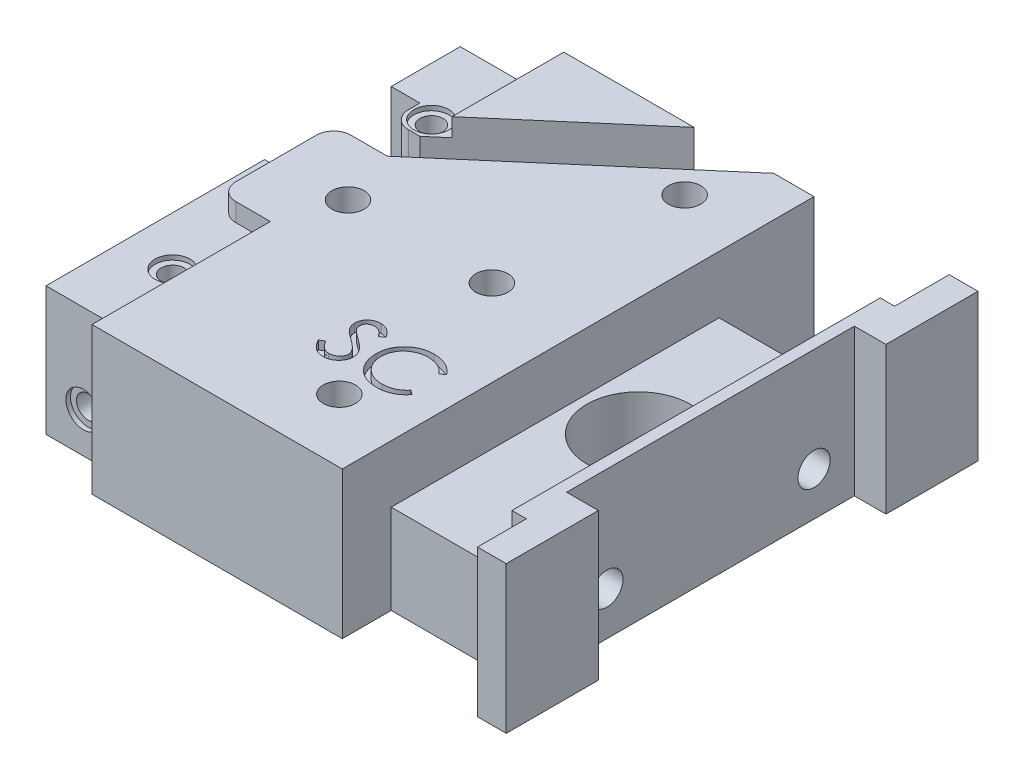
SolidWorks part; units mm, degrees
ref_plane "Plan de face" through (0, 0, 0) normal (0, 0, 1) x (1, 0, 0)
ref_plane "Plan de dessus" through (0, 0, 0) normal (0, 1, 0) x (1, 0, 0)
ref_plane "Plan de droite" through (0, 0, 0) normal (1, 0, 0) x (0, 0, -1)
sketch "Esquisse7" plane through (0, 0, 0) normal (0, 0, 1) x (1, 0, 0)
  line L2 (0, 0) -> (85, 0)
  line L3 (85, 0) -> (85, 25.55)
  line L5 (0, 25.55) -> (0, 0)
  line L6 (0, 25.55) -> (56.5, 25.55)
  line L7 (56.5, 25.55) -> (56.5, 15.55)
  line L8 (56.5, 15.55) -> (77.5, 15.55)
  line L9 (77.5, 15.55) -> (77.5, 25.55)
  line L10 (77.5, 25.55) -> (85, 25.55)
  dimension "D1" = 85
  dimension "D2" = 7.5
  dimension "D3" = 25.55
  dimension "D6" = 21
  dimension "D7" = 10
extrude "Boss.-Extru.3" add sketch "Esquisse7" along normal mid plane 82
sketch "Esquisse8" plane through (85, 0, 0) normal (1, 0, 0) x (0, 0, -1)
  line L0 (-41, 0) -> (41, 0) construction
  line L1 (-25, 0) -> (25, 0)
  line L2 (-25, 0) -> (-25, 25.55)
  line L3 (-25, 25.55) -> (25, 25.55)
  line L4 (25, 0) -> (25, 25.55)
  line L5 (-41, 25.55) -> (41, 25.55) construction
  point P8 (0, 0)
  point P9 (0, 0)
  dimension "D1" = 50
extrude "Enlèv. mat.-Extru.1" cut sketch "Esquisse8" against normal blind 5.5
sketch "Esquisse9" plane through (0, 15.55, 0) normal (0, 1, 0) x (1, 0, 0)
  line L0 (85, 25) -> (85, 41) construction
  circle A0 centre (67, 0) radius 9
  point P4 (85, 33)
  point P5 (67, 0)
  dimension "D1" = 18
  dimension "D2" = 18
extrude "Enlèv. mat.-Extru.2" cut sketch "Esquisse9" against normal through all
sketch "Esquisse10" plane through (0, 15.55, 0) normal (0, 1, 0) x (1, 0, 0)
  line L0 (56.5, -41) -> (56.5, 41) construction
  line L1 (77.5, 41) -> (56.5, 41)
  line L2 (77.5, 41) -> (77.5, 31.5)
  line L3 (77.5, 31.5) -> (56.5, 31.5)
  line L4 (56.5, 41) -> (56.5, 31.5)
  line L5 (56.5, 41) -> (0, 41) construction
  dimension "D1" = 9.5
  dimension "D2" = 21
extrude "Enlèv. mat.-Extru.3" cut sketch "Esquisse10" against normal through all
chamfer "Chanfrein1" distance 7 angle 45 1 edges at (67, 15.55, -31.5)
sketch "Esquisse13" plane through (0, 0, 41) normal (0, 0, 1) x (1, 0, 0)
  line L0 (0, 0) -> (85, 0) construction
  line L1 (56.5, 14) -> (77.5, 14)
  line L2 (56.5, 14) -> (56.5, 0)
  line L3 (56.5, 0) -> (77.5, 0)
  line L4 (77.5, 14) -> (77.5, 0)
  line L5 (77.5, 25.55) -> (77.5, 15.55) construction
  dimension "D1" = 21
  dimension "D2" = 14
extrude "Enlèv. mat.-Extru.5" [suppressed] cut sketch "Esquisse13" against normal blind 8.5
chamfer "Chanfrein2" [suppressed] distance 7 angle 45
sketch "Esquisse14" plane through (0, 25.55, 0) normal (0, 1, 0) x (1, 0, 0)
  line L0 (0, -41) -> (0, 41) construction
  line L1 (0, 41) -> (13, 41)
  line L2 (0, 41) -> (0, 10)
  line L3 (4, 10) -> (13, 10)
  line L4 (13, 41) -> (13, 10)
  line L5 (0, 0) -> (4, 0)
  line L6 (0, 0) -> (0, 10)
  line L8 (4, 0) -> (4, 10)
  dimension "D1" = 13
  dimension "D2" = 31
  dimension "D3" = 4
extrude "Enlèv. mat.-Extru.6" cut sketch "Esquisse14" against normal blind 3.175
sketch "Esquisse33" plane through (0, 0, 0) normal (-1, 0, 0) x (0, 0, 1)
  line L0 (41, 0) -> (-41, 0) construction
  line L1 (-24, 22.375) -> (-2, 22.375)
  line L2 (-24, 22.375) -> (-24, 0)
  line L3 (-24, 0) -> (-2, 0)
  line L4 (-2, 22.375) -> (-2, 0)
  line L5 (-41, 22.375) -> (0, 22.375) construction
  dimension "D2" = 22
  dimension "D3" = 2
extrude "Enlèv. mat.-Extru.20" cut sketch "Esquisse33" against normal blind 10
mirror "Symétrie1" about plane through (0, 0, 0) normal (0, 0, 1) of "Enlèv. mat.-Extru.6"
sketch "Esquisse34" plane through (0, 22.375, 0) normal (0, 1, 0) x (1, 0, 0)
  line L1 (10, 24) -> (5, 24)
  line L2 (10, 24) -> (10, 19)
  line L3 (10, 19) -> (5, 19)
  line L4 (5, 24) -> (5, 19)
  dimension "D1" = 5
  dimension "D2" = 5
extrude "Boss.-Extru.4" add sketch "Esquisse34" against normal up to surface (22.375 mm away) up to face at (67, 0, 9)
sketch "Esquisse16" plane through (0, 22.375, 0) normal (0, 1, 0) x (1, 0, 0)
  line L1 (4, 10) -> (13, 10) construction
  line L2 (13, 10) -> (13, 41) construction
  circle A0 centre (8.5, 22.5) radius 2
  dimension "D1" = 4
  dimension "D2" = 12.5
  dimension "D3" = 4.5
extrude "Enlèv. mat.-Extru.7" cut sketch "Esquisse16" against normal blind 10
sketch "Esquisse17" plane through (0, 22.375, 0) normal (0, 1, 0) x (1, 0, 0)
  circle A0 centre (8.5, 22.5) radius 3.05
  dimension "D1" = 6.1
extrude "Enlèv. mat.-Extru.8" cut sketch "Esquisse17" against normal blind 0.8
mirror "Symétrie2" about plane through (0, 0, 0) normal (0, 0, 1) of "Enlèv. mat.-Extru.8", "Enlèv. mat.-Extru.7"
sketch "Esquisse18" plane through (79.5, 0, 0) normal (1, 0, 0) x (0, 0, -1)
  line L0 (-25, 0) -> (25, 0) construction
  circle A0 centre (18, 7.55) radius 2.8
  dimension "D1" = 5.6
  dimension "D2" = 7.55
  dimension "D3" = 18
extrude "Enlèv. mat.-Extru.9" cut sketch "Esquisse18" against normal blind 12
mirror "Symétrie3" about plane through (0, 0, 0) normal (0, 0, 1) of "Enlèv. mat.-Extru.9"
sketch "Esquisse26" plane through (0, 0, -41) normal (0, 0, -1) x (-1, 0, 0)
  line L1 (0, 0) -> (-13, 0)
  line L2 (0, 0) -> (0, 22.375)
  line L3 (0, 22.375) -> (-13, 22.375)
  line L4 (-13, 0) -> (-13, 22.375)
extrude "Enlèv. mat.-Extru.13" cut sketch "Esquisse26" against normal blind 5
sketch "Esquisse27" plane through (0, 0, -36) normal (0, 0, -1) x (-1, 0, 0)
  line L0 (-6.5, 0) -> (-6.5, 7) construction
  line L1 (-13, 0) -> (0, 0) construction
  circle A0 centre (-6.5, 7) radius 2
  dimension "D1" = 4
  dimension "D2" = 7
extrude "Enlèv. mat.-Extru.14" cut sketch "Esquisse27" against normal blind 10 contours A0
sketch "Esquisse28" plane through (0, 0, -36) normal (0, 0, -1) x (-1, 0, 0)
  circle A0 centre (-6.5, 7) radius 3.05
  dimension "D1" = 6.1
extrude "Enlèv. mat.-Extru.15" cut sketch "Esquisse28" against normal blind 0.8
mirror "Symétrie4" about plane through (0, 0, 0) normal (0, 0, 1) of "Enlèv. mat.-Extru.15", "Enlèv. mat.-Extru.13", "Enlèv. mat.-Extru.14"
sketch "Esquisse29" plane through (0, 25.55, 0) normal (0, 1, 0) x (1, 0, 0)
  line L0 (41.5, 0) -> (16.5, 0) construction
  line L1 (56.5, -41) -> (56.5, 24.5) construction
  circle A0 centre (41.5, 0) radius 2.8
  circle A1 centre (16.5, 0) radius 2.8
  dimension "D1" = 5.6
  dimension "D2" = 25
  dimension "D3" = 15
extrude "Enlèv. mat.-Extru.16" cut sketch "Esquisse29" against normal blind 10
sketch "Esquisse30" plane through (0, 25.55, 0) normal (0, 1, 0) x (1, 0, 0)
  line L0 (56.5, -41) -> (56.5, 41) construction
  line L1 (65, -12.5) -> (48, -12.5)
  line L2 (65, -12.5) -> (65, 12.5)
  line L3 (65, 12.5) -> (48, 12.5)
  line L4 (48, -12.5) -> (48, 12.5)
  line L5 (65, -12.5) -> (48, 12.5) construction
  line L6 (65, 12.5) -> (48, -12.5) construction
  point P0 (56.5, 0)
  dimension "D1" = 25
  dimension "D2" = 17
extrude "Enlèv. mat.-Extru.17" [suppressed] cut sketch "Esquisse30" against normal blind 10
chamfer "Chanfrein4" [suppressed] distance 4 angle 45
sketch "Esquisse31" plane through (0, 25.55, 0) normal (0, 1, 0) x (1, 0, 0)
  line L0 (45, -30) -> (45, 30) construction
  line L1 (85, 25) -> (85, 41) construction
  circle A0 centre (45, -30) radius 2.8
  circle A1 centre (45, 30) radius 2.8
  point P4 (45, 0)
  dimension "D2" = 5.6
  dimension "D3" = 40
  dimension "D1" = 60
extrude "Enlèv. mat.-Extru.18" cut sketch "Esquisse31" against normal blind 10
sketch "Esquisse32" plane through (0, 0, 0) normal (0, -1, 0) x (1, 0, 0)
  line L0 (79.5, 25) -> (79.5, -25) construction
  line L1 (0, 0) -> (79.5, 0) construction
  line L2 (0, -15) -> (79.5, -15) construction
  line L3 (0, 15) -> (79.5, 15) construction
  circle A0 centre (11, 15) radius 2.8
  circle A1 centre (43, -15) radius 2.8
  dimension "D1" = 32
  dimension "D2" = 36.5
  dimension "D3" = 5.6
  dimension "D4" = 15
  dimension "D5" = 15
extrude "Enlèv. mat.-Extru.19" cut sketch "Esquisse32" against normal blind 10
fillet "Congé1" radius 3 1 edges at (5, 11.1875, -19)
sketch "Esquisse35" plane through (0, 25.55, 0) normal (0, 1, 0) x (1, 0, 0)
  line L0 (4, 2) -> (49.4846, 41)
  line L1 (56.5, 41) -> (13, 41) construction
  line L2 (49.4846, 41) -> (35.658, 41)
  line L3 (35.658, 41) -> (10, 19)
  line L4 (4, 2) -> (4, 10)
  line L5 (4, 10) -> (10, 19)
  dimension "D1" = 9
extrude "Enlèv. mat.-Extru.21" cut sketch "Esquisse35" against normal blind 16
sketch "Esquisse36" plane through (0, 25.55, 0) normal (0, 1, 0) x (1, 0, 0)
  line L0 (4, 1.9828) -> (4, 10)
  line L1 (4, -10) -> (4, 2) construction
  line L2 (4, 10) -> (13.3302, 10)
  line L3 (4, 2) -> (49.4846, 41) construction
  line L4 (13.3302, 10) -> (4, 1.9828)
  line L5 (4, -10) -> (13, -10) construction
  dimension "D1" = 20
extrude "Boss.-Extru.5" add sketch "Esquisse36" against normal up to surface (3.175 mm away) up to face at (8, 22.375, -3.7149)
sketch "Esquisse37" plane through (0, 25.55, 0) normal (0, 1, 0) x (1, 0, 0)
  line L0 (56.5, 31.5) -> (77.5, 31.5) construction
  line L1 (77.5, 41) -> (80, 41)
  line L2 (77.5, 41) -> (77.5, 31.5)
  line L3 (77.5, 31.5) -> (80, 31.5)
  line L4 (80, 41) -> (80, 31.5)
  dimension "D1" = 2.5
extrude "Enlèv. mat.-Extru.22" cut sketch "Esquisse37" against normal through all
sketch "Esquisse38" plane through (0, 25.55, 0) normal (0, 1, 0) x (1, 0, 0)
  line L0 (49.4846, 41) -> (41.0874, 33.8)
  line L1 (10, 7.1446) -> (49.4846, 41) construction
  line L2 (41.0874, 33.8) -> (27.2608, 33.8)
  line L3 (35.658, 41) -> (10, 19) construction
  line L4 (27.2608, 33.8) -> (35.658, 41)
  line L5 (35.658, 41) -> (49.4846, 41)
  line L6 (35.658, 41) -> (13, 41) construction
  dimension "D1" = 7.2
extrude "Enlèv. mat.-Extru.23" cut sketch "Esquisse38" against normal through all
chamfer "Chanfrein5" distance 2 angle 45 1 edges at (34.1741, 9.55, -33.8)
sketch "Esquisse39" plane through (0, 25.55, 0) normal (0, 1, 0) x (1, 0, 0)
  line L0 (13, -25.5) -> (56.5, -25.5) construction
  line L1 (13, -10) -> (13, -41) construction
  line L2 (56.5, -41) -> (56.5, 41) construction
  text T0 "SC" font "Century Gothic" height in points 36
extrude "Enlèv. mat.-Extru.24" cut sketch "Esquisse39" against normal blind 1.5
sketch "Esquisse40" plane through (0, 0, 0) normal (0, -1, 0) x (1, 0, 0)
  line L0 (0, 33.2) -> (37, 33.2)
  line L1 (0, 33.2) -> (0, 31)
  line L2 (37, 33.2) -> (37, 31)
  line L3 (0, 31) -> (37, 31)
  line L4 (0, 36) -> (0, -2) construction
  line L5 (13, 41) -> (85, 41) construction
  point P6 (37, 32.1)
  dimension "D1" = 37
  dimension "D2" = 2.2
  dimension "D3" = 8.9
sketch "Esquisse41" plane through (0, 0, 0) normal (0, -1, 0) x (1, 0, 0)
  line L0 (10, -2) -> (0, -2)
  line L1 (10, -2) -> (10, -0.9985)
  line L2 (0, -2) -> (0, -0.9985)
  line L3 (10, -0.9985) -> (0, -0.9985)
sketch "Esquisse42" plane through (0, 15.55, 0) normal (0, 1, 0) x (1, 0, 0)
  line L0 (56.5, -41) -> (77.5, -41)
  line L1 (56.5, -41) -> (56.5, -32.5)
  line L2 (77.5, -41) -> (77.5, -32.5)
  line L3 (56.5, -32.5) -> (77.5, -32.5)
  dimension "D1" = 8.5
extrude "Enlèv. mat.-Extru.27" cut sketch "Esquisse42" against normal up to next
sketch "Esquisse43" plane through (0, 25.55, 0) normal (0, 1, 0) x (1, 0, 0)
  line L0 (77.5, -41) -> (77.5, -32.5)
  line L1 (77.5, -41) -> (80, -41)
  line L2 (77.5, -32.5) -> (80, -32.5)
  line L3 (80, -41) -> (80, -32.5)
  dimension "D1" = 2.5
extrude "Enlèv. mat.-Extru.28" cut sketch "Esquisse43" against normal up to next
fillet "Congé2" radius 3 2 edges at (4, 23.9625, 10) (4, 23.9625, -10)
